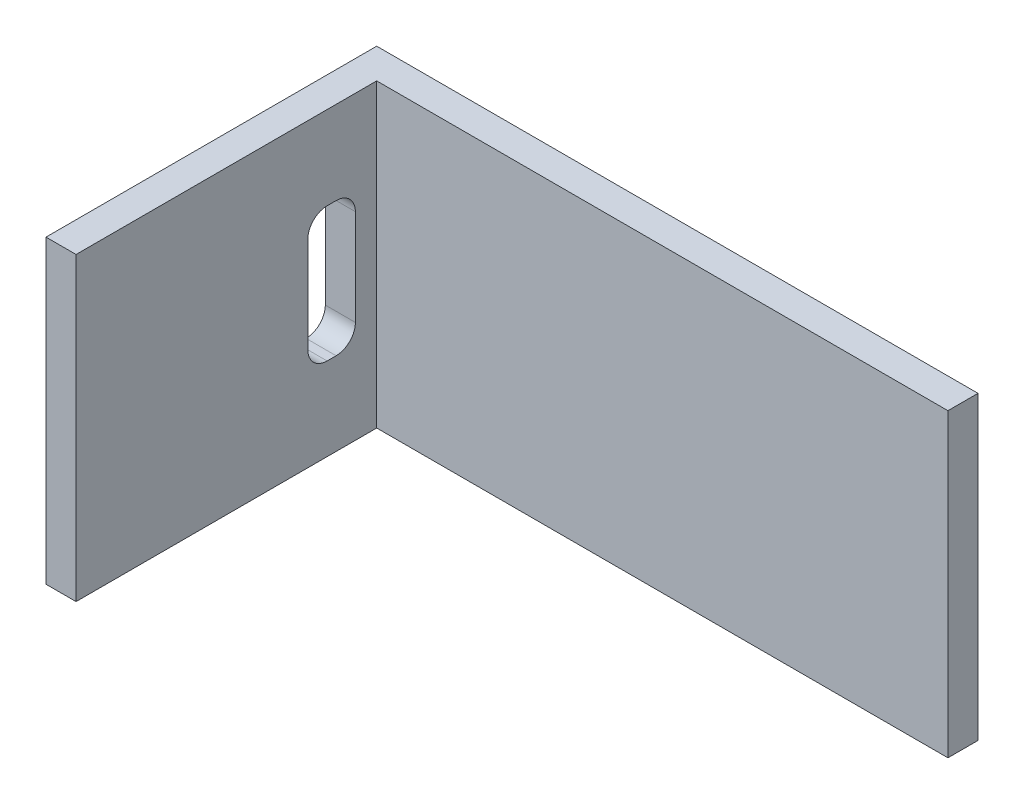
SolidWorks part; units mm, degrees
ref_plane "Спереди" through (0, 0, 0) normal (0, 0, 1) x (1, 0, 0)
ref_plane "Сверху" through (0, 0, 0) normal (0, 1, 0) x (1, 0, 0)
ref_plane "Справа" through (0, 0, 0) normal (1, 0, 0) x (0, 0, -1)
sketch "Эскиз1" plane through (0, 0, 0) normal (0, 0, 1) x (1, 0, 0)
  line L1 (0, 0) -> (40, 0)
  line L2 (0, 0) -> (0, 20)
  line L3 (0, 20) -> (40, 20)
  line L4 (40, 0) -> (40, 20)
  dimension "D1" = 40
  dimension "D2" = 20
extrude "Бобышка-Вытянуть1" add sketch "Эскиз1" along normal blind 2
sketch "Эскиз2" plane through (0, 0, 2) normal (0, 0, 1) x (1, 0, 0)
  line L0 (0, 0) -> (40, 0) construction
  line L1 (0, 20) -> (2, 20)
  line L2 (0, 20) -> (0, 0)
  line L3 (0, 0) -> (2, 0)
  line L4 (2, 20) -> (2, 0)
  dimension "D1" = 2
extrude "Бобышка-Вытянуть2" add sketch "Эскиз2" along normal blind 20
sketch "Эскиз5" plane through (2, 0, 0) normal (1, 0, 0) x (0, 0, -1)
  line L8 (-4.6992, 14.4542) -> (-5.2992, 14.4542)
  line L9 (-6.5792, 13.1742) -> (-6.5792, 6.7942)
  line L10 (-5.2992, 5.5142) -> (-4.6992, 5.5142)
  line L11 (-3.4192, 6.7942) -> (-3.4192, 13.1742)
  arc A8 (-3.4192, 13.1742) -> (-4.6992, 14.4542) centre (-4.6992, 13.1742) ccw
  arc A9 (-5.2992, 14.4542) -> (-6.5792, 13.1742) centre (-5.2992, 13.1742) ccw
  arc A10 (-6.5792, 6.7942) -> (-5.2992, 5.5142) centre (-5.2992, 6.7942) ccw
  arc A11 (-4.6992, 5.5142) -> (-3.4192, 6.7942) centre (-4.6992, 6.7942) ccw
  point P10 (0, 0)
  point P15 (0, 0)
extrude "Вырез-Вытянуть1" cut sketch "Эскиз5" against normal blind 20
